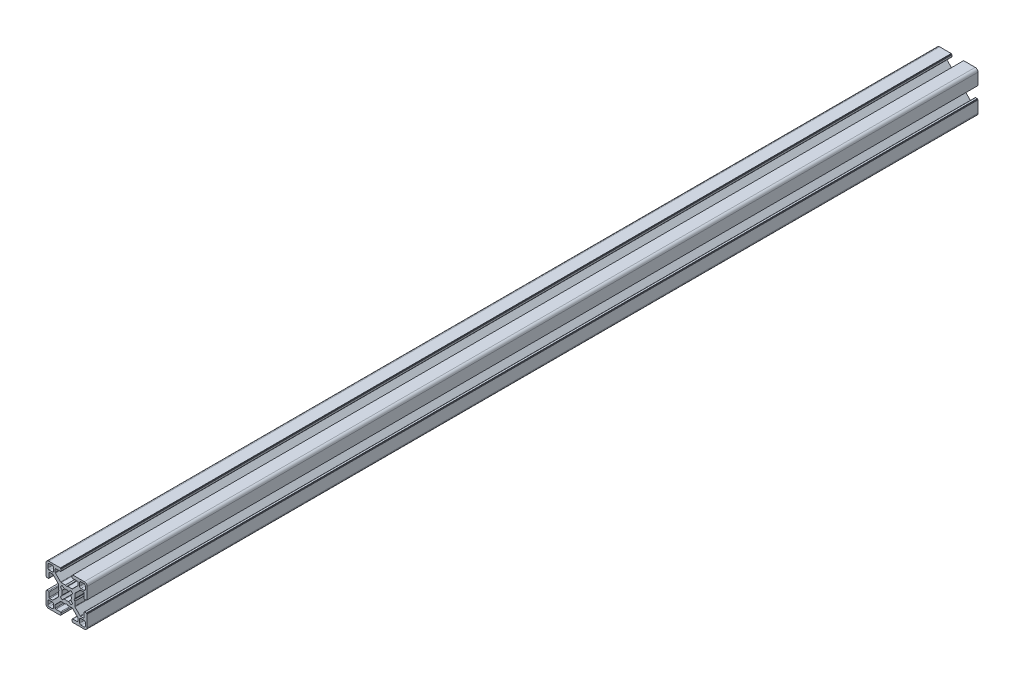
SolidWorks part; units mm, degrees
ref_plane "Front Plane" through (0, 0, 0) normal (0, 0, 1) x (1, 0, 0)
ref_plane "Top Plane" through (0, 0, 0) normal (0, 1, 0) x (1, 0, 0)
ref_plane "Right Plane" through (0, 0, 0) normal (1, 0, 0) x (0, 0, -1)
sketch "Sketch1" plane through (0, 0, 0) normal (0, 0, 1) x (1, 0, 0)
  line L0 (-15, 0) -> (15, 0) construction
  line L1 (0, -15) -> (0, 15) construction
  line L2 (-4.5, 15) -> (4.5, 15) construction
  line L3 (-4, -15) -> (4, -15) construction
  line L4 (-4.5, 15) -> (-4.5, 14.5)
  line L5 (-4.5, 14.5) -> (-4, 14.5)
  line L6 (-4, 14.5) -> (-4, 13.29)
  line L7 (-4.5, 12.79) -> (-7.7675, 12.79)
  line L8 (-8.2675, 12.29) -> (-8.2675, 10.2707)
  line L9 (-8.1211, 9.9171) -> (-4.3504, 6.1464)
  line L10 (-3.9968, 6) -> (0, 6)
  line L11 (0, 0) -> (-15, 15) construction
  line L12 (-4.5, 15) -> (-12.968, 15)
  line L14 (-12.705, 9.5135) -> (-10.5135, 9.5135)
  line L15 (-13.705, 10.5135) -> (-13.705, 12.705)
  line L16 (-12.705, 13.705) -> (-10.5135, 13.705)
  line L17 (-9.5135, 10.5135) -> (-9.5135, 12.705)
  line L18 (-13.705, 9.5135) -> (-9.5135, 13.705) construction
  line L19 (-13.705, 13.705) -> (-9.5135, 9.5135) construction
  line L20 (-3.1568, 4.5038) -> (-1.5303, 3.1477) construction
  line L21 (-4.5038, 3.1568) -> (-3.1477, 1.5303) construction
  line L22 (-6, 3.9968) -> (-6, 0)
  line L23 (-9.9171, 8.1211) -> (-6.1464, 4.3504)
  line L24 (-15, 4.5) -> (-15, 12.968)
  line L25 (-12.29, 8.2675) -> (-10.2707, 8.2675)
  line L26 (-12.79, 4.5) -> (-12.79, 7.7675)
  line L27 (-14.5, 4) -> (-13.29, 4)
  line L28 (-14.5, 4.5) -> (-14.5, 4)
  line L29 (-15, 4.5) -> (-14.5, 4.5)
  circle A0 centre (0, 0) radius 3.5
  arc A1 (-12.968, 15) -> (-15, 12.968) centre (-12.968, 12.968) ccw
  circle A2 centre (0, 0) radius 5.5 construction
  arc A3 (-10.5135, 9.5135) -> (-9.5135, 10.5135) centre (-10.5135, 10.5135) ccw
  arc A4 (-13.705, 12.705) -> (-12.705, 13.705) centre (-12.705, 12.705) cw
  arc A5 (-10.5135, 13.705) -> (-9.5135, 12.705) centre (-10.5135, 12.705) cw
  arc A6 (-12.705, 9.5135) -> (-13.705, 10.5135) centre (-12.705, 10.5135) cw
  arc A7 (-12.79, 4.5) -> (-13.29, 4) centre (-13.29, 4.5) cw
  arc A8 (-12.29, 8.2675) -> (-12.79, 7.7675) centre (-12.29, 7.7675) ccw
  arc A9 (-9.9171, 8.1211) -> (-10.2707, 8.2675) centre (-10.2707, 7.7675) ccw
  arc A10 (-6, 3.9968) -> (-6.1464, 4.3504) centre (-6.5, 3.9968) ccw
  arc A11 (-4.3504, 6.1464) -> (-3.9968, 6) centre (-3.9968, 6.5) ccw
  arc A12 (-4, 13.29) -> (-4.5, 12.79) centre (-4.5, 13.29) cw
  arc A13 (-7.7675, 12.79) -> (-8.2675, 12.29) centre (-7.7675, 12.29) ccw
  arc A14 (-8.2675, 10.2707) -> (-8.1211, 9.9171) centre (-7.7675, 10.2707) ccw
  point P4 (0, 0)
  point P8 (0, 0)
  point P13 (0, 15)
  point P15 (0, -15)
  point P16 (0, 6)
  point P23 (-11.6092, 11.6093)
  point P26 (0, 6)
  point P62 (-12.79, 4)
  point P65 (-12.79, 8.2675)
  point P68 (-10.0636, 8.2675)
  point P71 (-6, 4.2039)
  point P74 (-4.2039, 6)
  point P77 (-4, 12.79)
  point P80 (-8.2675, 12.79)
  point P83 (-8.2675, 10.0636)
  dimension "Center Hole Diameter" = 7
  dimension "D11" = 2.032
  dimension "D9" = 11
  dimension "D13" = 1
  dimension "D14" = 0.5
  dimension "Rail Height" = 30
  dimension "Rail Width" = 30
  dimension "T-Slot Width" = 8
  dimension "T-Slot Depth" = 9
  dimension "D1" = 9
  dimension "D2" = 45
  dimension "D3" = 8
  dimension "D4" = 2.21
  dimension "D5" = 16.535
  dimension "D7" = 2.54
  dimension "D6" = 1.295
  dimension "D8" = 1.246
  dimension "D10" = 10.36
  dimension "D12" = 1.905
sketch "Sketch2" plane through (0, 0, 0) normal (1, 0, 0) x (0, 0, -1)
  line L0 (-76.2, 0) -> (76.2, 0) construction
  line L2 (0, -15) -> (0, 15) construction
  line L3 (0, -15) -> (0, 15) construction
  line L4 (-76.2, -15) -> (-76.2, 15) construction
  line L5 (76.2, -15) -> (76.2, 15) construction
  point P0 (-38.7, 0)
  point P3 (0, 0)
  point P4 (38.7, 0)
  point P12 (-76.2, 0)
  point P14 (76.2, 0)
  dimension "Length" = 152.4
  dimension "D1" = 37.5
sketch "Sketch3" plane through (0, 0, 0) normal (0, 0, 1) x (1, 0, 0)
  line L0 (-4.5038, 3.1568) -> (-3.1477, 1.5303)
  line L1 (0, 3.5) -> (0, 5.5)
  line L2 (-5.5, 0) -> (-3.5, 0)
  line L7 (-6, 3.9968) -> (-6, 0) construction
  line L31 (-9.9171, 8.1211) -> (-6.1464, 4.3504) construction
  line L117 (-12.29, 8.2675) -> (-10.2707, 8.2675) construction
  line L118 (-12.79, 4.5) -> (-12.79, 7.7675) construction
  line L157 (-12.705, 9.5135) -> (-10.5135, 9.5135)
  line L158 (-9.5135, 10.5135) -> (-9.5135, 12.705)
  line L163 (-10.5135, 13.705) -> (-12.705, 13.705)
  line L164 (-13.705, 12.705) -> (-13.705, 10.5135)
  line L165 (-12.705, 9.5135) -> (-10.5135, 9.5135)
  line L166 (-9.5135, 10.5135) -> (-9.5135, 12.705)
  line L167 (-10.5135, 13.705) -> (-12.705, 13.705)
  line L168 (-13.705, 12.705) -> (-13.705, 10.5135)
  line L169 (-14.5, 4) -> (-13.29, 4) construction
  line L170 (-14.5, 4.5) -> (-14.5, 4) construction
  line L171 (-15, 4.5) -> (-14.5, 4.5) construction
  line L172 (-15, 4.5) -> (-15, 12.968) construction
  line L173 (-4.5, 15) -> (-12.968, 15) construction
  line L174 (-4.5, 15) -> (-4.5, 14.5) construction
  line L175 (-4.5, 14.5) -> (-4, 14.5) construction
  line L176 (-4, 14.5) -> (-4, 13.29) construction
  line L177 (-4.5, 12.79) -> (-7.7675, 12.79) construction
  line L178 (-8.2675, 12.29) -> (-8.2675, 10.2707) construction
  line L179 (-8.1211, 9.9171) -> (-4.3504, 6.1464) construction
  line L180 (-3.9968, 6) -> (0, 6) construction
  line L181 (-6, 3.9968) -> (-6, 0.866)
  line L182 (-9.9171, 8.1211) -> (-6.1464, 4.3504)
  line L183 (-12.29, 8.2675) -> (-10.2707, 8.2675)
  line L184 (-12.79, 4.5) -> (-12.79, 7.7675)
  line L185 (-14.5, 4) -> (-13.29, 4)
  line L186 (-14.5, 4.5) -> (-14.5, 4)
  line L187 (-15, 4.5) -> (-14.5, 4.5)
  line L188 (-15, 4.5) -> (-15, 12.968)
  line L189 (-4.5, 15) -> (-12.968, 15)
  line L190 (-4.5, 15) -> (-4.5, 14.5)
  line L191 (-4.5, 14.5) -> (-4, 14.5)
  line L192 (-4, 14.5) -> (-4, 13.29)
  line L193 (-4.5, 12.79) -> (-7.7675, 12.79)
  line L194 (-8.2675, 12.29) -> (-8.2675, 10.2707)
  line L195 (-8.1211, 9.9171) -> (-4.3504, 6.1464)
  line L196 (-3.9968, 6) -> (-0.866, 6)
  line L197 (-0.866, 6) -> (0, 5.5)
  line L198 (0, -15) -> (0, 15) construction
  line L199 (0, 0) -> (-15, 15) construction
  line L200 (0, 0) -> (-15, 15) construction
  line L201 (-3.1568, 4.5038) -> (-1.5303, 3.1477) construction
  line L202 (-3.1568, 4.5038) -> (-1.5303, 3.1477)
  line L203 (-6, 0.866) -> (-5.5, 0)
  line L204 (-15, 0) -> (15, 0) construction
  line L205 (-15, 0) -> (15, 0) construction
  line L206 (0, -15) -> (0, 15) construction
  arc A0 (-3.5, 0) -> (-3.1477, 1.5303) centre (0, 0) cw
  arc A10 (-6, 3.9968) -> (-6.1464, 4.3504) centre (-6.5, 3.9968) ccw construction
  circle A16 centre (0, 0) radius 3.5
  arc A18 (0, 3.5) -> (-1.5303, 3.1477) centre (0, 0) ccw
  arc A20 (-9.9171, 8.1211) -> (-10.2707, 8.2675) centre (-10.2707, 7.7675) ccw construction
  arc A22 (-12.29, 8.2675) -> (-12.79, 7.7675) centre (-12.29, 7.7675) ccw construction
  arc A28 (-13.29, 4) -> (-12.79, 4.5) centre (-13.29, 4.5) ccw construction
  arc A29 (-10.5135, 9.5135) -> (-9.5135, 10.5135) centre (-10.5135, 10.5135) ccw
  arc A30 (-9.5135, 12.705) -> (-10.5135, 13.705) centre (-10.5135, 12.705) ccw
  arc A31 (-12.705, 13.705) -> (-13.705, 12.705) centre (-12.705, 12.705) ccw
  arc A32 (-13.705, 10.5135) -> (-12.705, 9.5135) centre (-12.705, 10.5135) ccw
  arc A33 (-10.5135, 9.5135) -> (-9.5135, 10.5135) centre (-10.5135, 10.5135) ccw
  arc A34 (-9.5135, 12.705) -> (-10.5135, 13.705) centre (-10.5135, 12.705) ccw
  arc A35 (-12.705, 13.705) -> (-13.705, 12.705) centre (-12.705, 12.705) ccw
  arc A36 (-13.705, 10.5135) -> (-12.705, 9.5135) centre (-12.705, 10.5135) ccw
  arc A37 (-12.968, 15) -> (-15, 12.968) centre (-12.968, 12.968) ccw construction
  arc A38 (-4.5, 12.79) -> (-4, 13.29) centre (-4.5, 13.29) ccw construction
  arc A39 (-7.7675, 12.79) -> (-8.2675, 12.29) centre (-7.7675, 12.29) ccw construction
  arc A40 (-8.2675, 10.2707) -> (-8.1211, 9.9171) centre (-7.7675, 10.2707) ccw construction
  arc A41 (-4.3504, 6.1464) -> (-3.9968, 6) centre (-3.9968, 6.5) ccw construction
  arc A42 (-6, 3.9968) -> (-6.1464, 4.3504) centre (-6.5, 3.9968) ccw
  arc A43 (-9.9171, 8.1211) -> (-10.2707, 8.2675) centre (-10.2707, 7.7675) ccw
  arc A44 (-12.29, 8.2675) -> (-12.79, 7.7675) centre (-12.29, 7.7675) ccw
  arc A45 (-13.29, 4) -> (-12.79, 4.5) centre (-13.29, 4.5) ccw
  arc A46 (-12.968, 15) -> (-15, 12.968) centre (-12.968, 12.968) ccw
  arc A47 (-4.5, 12.79) -> (-4, 13.29) centre (-4.5, 13.29) ccw
  arc A48 (-7.7675, 12.79) -> (-8.2675, 12.29) centre (-7.7675, 12.29) ccw
  arc A49 (-8.2675, 10.2707) -> (-8.1211, 9.9171) centre (-7.7675, 10.2707) ccw
  arc A50 (-4.3504, 6.1464) -> (-3.9968, 6) centre (-3.9968, 6.5) ccw
  circle A51 centre (0, 0) radius 5.5 construction
  arc A52 (-3.1568, 4.5038) -> (-4.5038, 3.1568) centre (0, 0) ccw
  dimension "D3" = 60
  dimension "D4" = 60
  dimension "D1" = 0
  dimension "D2" = 0
extrude "Boss-Extrude1" add sketch "Sketch3" along normal mid plane 650
pattern_circular "CirPattern1" count 4 over 360 about axis through (0, 0, 0) along (0, 0, 1) of "Boss-Extrude1"
ref_plane "Contact Plane1" through (15, 0, 0) normal (1, 0, 0) x (0, 0, -1)
ref_plane "Contact Plane2" through (0, -15, 0) normal (0, 1, 0) x (1, 0, 0)
ref_plane "Contact Plane3" through (-15, 0, 0) normal (1, 0, 0) x (0, 0, -1)
ref_plane "Contact Plane4" through (0, 15, 0) normal (0, 1, 0) x (1, 0, 0)
equation "\"D1@Sketch2\" = \"Rail Height@Sketch1\" * 1.25"
equation "\"D1@Sketch1\"=\"T-Slot Width@Sketch1\"+1mm"
equation "\"D3@Sketch1\"=\"T-Slot Width@Sketch1\""
equation "\"D1@Boss-Extrude1\"=\"length\""
equation "\"length\" = 650"
